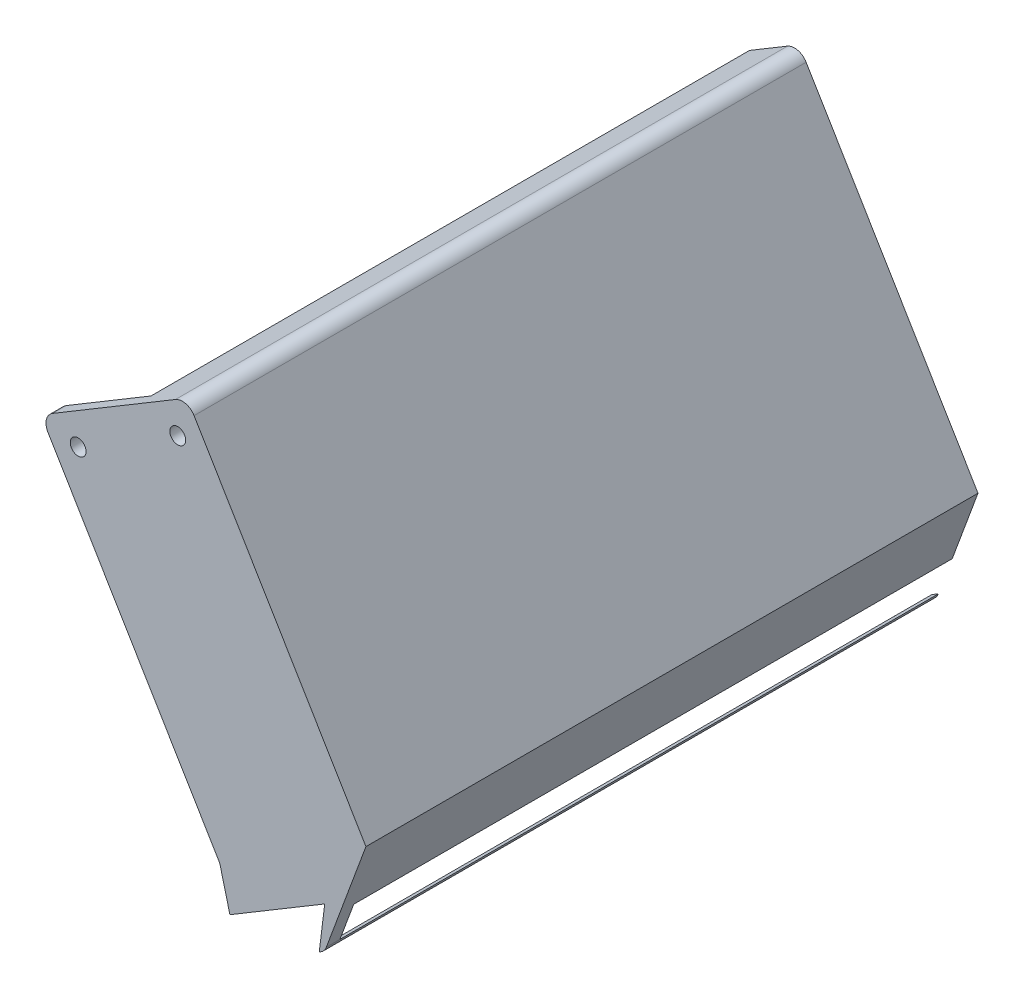
SolidWorks part; units mm, degrees
ref_plane "前视基准面" through (0, 0, 0) normal (0, 0, 1) x (1, 0, 0)
ref_plane "上视基准面" through (0, 0, 0) normal (0, 1, 0) x (1, 0, 0)
ref_plane "右视基准面" through (0, 0, 0) normal (1, 0, 0) x (0, 0, -1)
other "Configuration Table"
sketch "草图1" plane through (0, 0, 0) normal (0, 0, 1) x (1, 0, 0)
  line L0 (-25.9417, 62.2117) -> (-47.9555, 49.0437) construction
  line L1 (-13.5224, 69.6405) -> (-19.9321, 80.3561) construction
  line L3 (-7.6353, 71.4867) -> (-46.361, 136.2271)
  line L4 (-50.4755, 137.2617) -> (-77.6384, 121.0137)
  line L5 (-78.6729, 116.8991) -> (-40.9084, 53.7656)
  line L11 (-47.5232, 39.2152) -> (-17.4864, 57.1817) construction
  line L12 (-47.5232, 39.2152) -> (-32.1233, 13.4695) construction
  line L14 (-47.5232, 39.2152) -> (-17.4864, 57.1817)
  line L15 (-47.5232, 39.2152) -> (-39.8232, 26.3424)
  line L16 (-20.3097, 47.1456) -> (-18.7455, 46.9531)
  line L18 (-37.974, 43.3273) -> (-30.9788, 31.6326)
  line L19 (-15.2332, 46.5207) -> (9.4257, 43.4855) construction
  line L20 (-33.3885, 35.6611) -> (-23.2789, 18.7598) construction
  line L21 (-47.5232, 39.2152) -> (-32.1233, 13.4695) construction
  line L22 (-17.4864, 57.1817) -> (10.6847, 53.7141) construction
  line L23 (-30.9788, 31.6326) -> (-39.8232, 26.3424)
  line L25 (-38.3052, 44.1213) -> (-40.5772, 52.9715)
  line L26 (-7.8739, 74.0688) -> (-17.13, 49.0811)
  line L27 (-33.3885, 35.6611) -> (-15.2332, 46.5207) construction
  line L28 (-17.4864, 57.1817) -> (-18.7455, 46.9531)
  line L29 (-38.3052, 44.1213) -> (-17.13, 49.0811) construction
  arc A0 (-20.3097, 47.1456) -> (-17.13, 49.0811) centre (-19.9432, 50.1231) ccw
  circle A1 centre (-71.9838, 117.4046) radius 1.75
  circle A2 centre (-71.9838, 117.4046) radius 1.75
  circle A3 centre (-49.9701, 130.5725) radius 1.75
  circle A4 centre (-49.9701, 130.5725) radius 1.75
  arc A5 (-38.3052, 44.1213) -> (-37.974, 43.3273) centre (-35.3994, 44.8673) ccw
  arc A6 (-40.9084, 53.7656) -> (-40.5772, 52.9715) centre (-43.483, 52.2255) cw
  arc A7 (-7.6353, 71.4867) -> (-7.8739, 74.0688) centre (-5.0607, 73.0267) ccw
  arc A8 (-46.361, 136.2271) -> (-50.4755, 137.2617) centre (-48.9355, 134.6871) ccw
  arc A9 (-77.6384, 121.0137) -> (-78.6729, 116.8991) centre (-76.0984, 118.4391) ccw
  point P35 (-40.6853, 53.3925)
  point P40 (-8.3733, 72.7205)
  point P43 (-47.901, 138.8017)
  point P46 (-80.213, 119.4737)
  dimension "D4" = 3
  dimension "D3" = 6
  dimension "D5" = 6
  dimension "D6" = 6
  dimension "D8" = 37.6515
  dimension "D1" = 0
  dimension "D2" = 0
extrude "凸台-拉伸1" add sketch "草图1" along normal up to surface (135.2938 mm away) contours L4 A9 L5 A6 L25 A5 L18 L23 L15 L14 L28 L16 A0 L26 A7 L3 A8 A2 A4
sketch "草图2" plane through (-31.0503, 11.5018, 0) normal (0.9377, -0.3474, 0) x (-0.3474, -0.9377, 0)
  line L1 (-40.0746, -135.2938) -> (-40.0746, 0) construction
  line L2 (-40.0746, -135.2938) -> (-40.0746, 0)
sketch "草图3" plane through (14.8864, 8.9043, 0) normal (0.8582, 0.5133, 0) x (0, 0, -1)
  line L0 (-135.2938, 50.9143) -> (0, 50.9143) construction
  line L1 (-132.2938, 50.9143) -> (1.7062, 50.9143)
  line L2 (-135.2938, 127.6719) -> (-135.2938, 142.4272) construction
  line L3 (4.7062, 142.4253) -> (4.7062, 127.7102) construction
  line L4 (1.7062, 143.7074) -> (1.7062, 50.9143)
  line L5 (-135.2938, 143.7074) -> (0, 143.7074) construction
  line L6 (1.7062, 143.7074) -> (-132.2938, 143.7074)
  line L7 (-132.2938, 143.7074) -> (-132.2938, 50.9143)
  dimension "D1" = 3
  dimension "D2" = 3
extrude "切除-拉伸1" cut sketch "草图3" against normal through all
